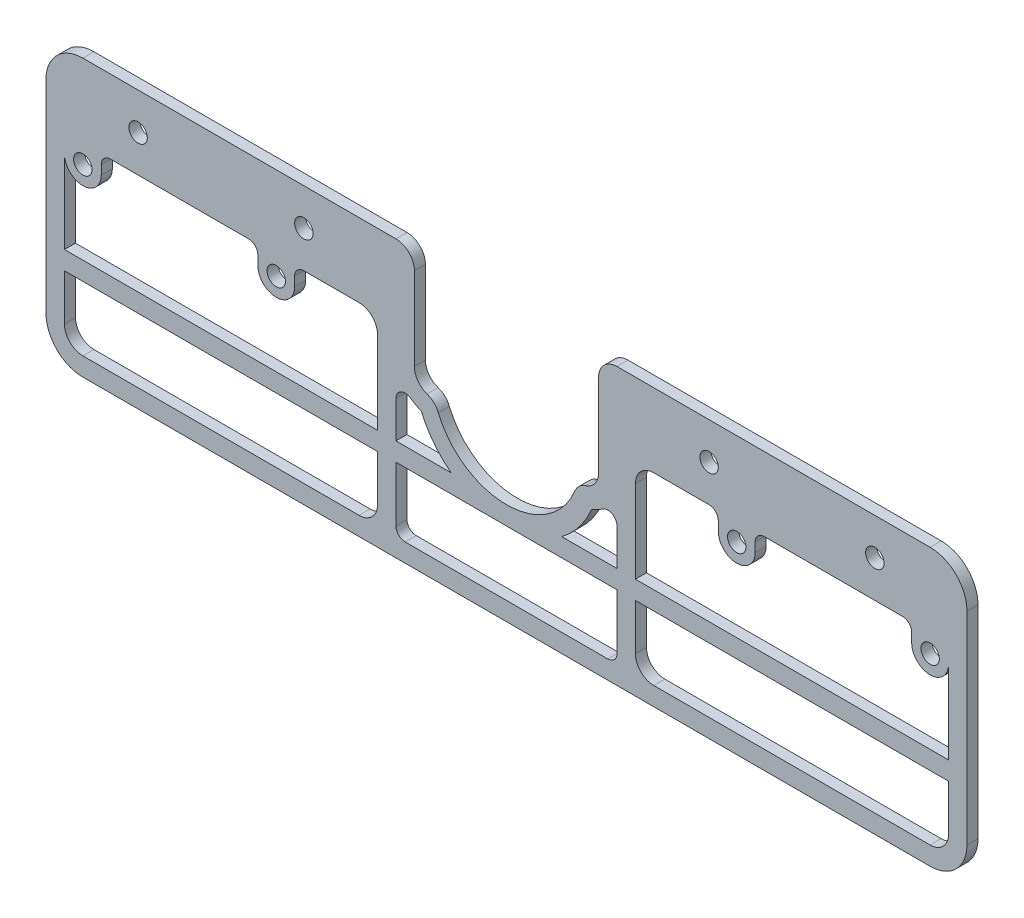
SolidWorks part; units mm, degrees
ref_plane "Front Plane" through (0, 0, 0) normal (0, 0, 1) x (1, 0, 0)
ref_plane "Top Plane" through (0, 0, 0) normal (0, 1, 0) x (1, 0, 0)
ref_plane "Right Plane" through (0, 0, 0) normal (1, 0, 0) x (0, 0, -1)
sketch "Sketch1" plane through (0, 0, 0) normal (0, 0, 1) x (1, 0, 0)
  line L0 (-40, 20) -> (-40, 55) construction
  line L4 (-250, -55) -> (-250, 3.1783)
  line L8 (-50, 75) -> (-230, 75) construction
  line L17 (0, -20) -> (0, -40)
  line L25 (0, -65) -> (0, -75)
  line L26 (0, 75) -> (0, -75) construction
  line L27 (-50, 95) -> (50, 95) construction
  line L34 (0, -75) -> (-230, -75)
  line L156 (-50, 75) -> (-230, 75) construction
  line L161 (0, -40) -> (0, -65)
  line L165 (-164.3309, 75) -> (-60, 75)
  line L167 (-230, 75) -> (-220, 75)
  line L171 (-250, 3.1783) -> (-250, 55)
  line L172 (-220, 75) -> (-164.3309, 75)
  line L173 (-50, 65) -> (-50, 20)
  arc A0 (-40, 20) -> (0, -20) centre (0, 20) ccw construction
  circle A1 centre (0, 20) radius 30 construction
  arc A4 (-230, -75) -> (-250, -55) centre (-230, -55) cw
  arc A5 (-250, 55) -> (-230, 75) centre (-230, 55) cw
  arc A124 (0, -20) -> (-37, 4.8013) centre (0, 20) cw
  arc A125 (-60, 75) -> (-50, 65) centre (-60, 65) cw
  arc A126 (-43.125, 10.5008) -> (-50, 20) centre (-40, 20) cw
  arc A127 (-37, 4.8013) -> (-43.125, 10.5008) centre (-46.25, 1.0016) ccw
  point P0 (0, 0)
  point P10 (-50, 10)
  point P11 (0, 50)
  point P30 (-40, 75)
  point P45 (0, -30)
  point P74 (0, 95)
  dimension "D3" = 80
  dimension "D4" = 60
  dimension "D6" = 55
  dimension "D7" = 75
  dimension "D10" = 10
  dimension "D11" = 20
  dimension "D8" = 10
  dimension "D5" = 10
  dimension "D9" = 20
  dimension "D13" = 210
  dimension "D16" = 100
  dimension "D17" = 20
  dimension "D26" = 250
extrude "Boss-Extrude1" add sketch "Sketch1" along normal blind 6
mirror "Mirror1" about plane through (0, -20, 6) normal (-1, 0, 0) of "Boss-Extrude1"
sketch "Sketch3" plane through (0, 0, 6) normal (0, 0, 1) x (1, 0, 0)
  line L3 (50, 20) -> (50, 65) construction
  line L4 (50, 20) -> (50, 65) construction
  line L7 (-60, 75) -> (-230, 75) construction
  line L8 (-250, 55) -> (-250, -55) construction
  line L9 (250, 55) -> (250, -55) construction
  circle A2 centre (110, 55) radius 5
  circle A3 centre (200, 55) radius 5
  circle A4 centre (-200, 55) radius 5
  circle A5 centre (-110, 55) radius 5
  dimension "D3" = 10
  dimension "D4" = 10
  dimension "D5" = 10
  dimension "D6" = 10
  dimension "D8" = 20
  dimension "D12" = 50
  dimension "D2" = 140
  dimension "D7" = 20
  dimension "D9" = 50
  dimension "D10" = 140
extrude "Cut-Extrude1" cut sketch "Sketch3" against normal through all contours A2 | A3 | A5 | A4
sketch "Sketch4" plane through (0, 0, 6) normal (0, 0, 1) x (1, 0, 0)
  line L0 (-230, -75) -> (230, -75) construction
  line L1 (-70, 25) -> (-70, -55)
  line L2 (-50, 20) -> (-50, 65) construction
  line L3 (-60, 75) -> (-230, 75) construction
  line L7 (-240, -55) -> (-240, 25)
  line L8 (-250, 55) -> (-250, -55) construction
  line L9 (-210, -65) -> (-190, -65)
  line L10 (-115, 25) -> (-115, 30)
  line L11 (-110, 35) -> (-80, 35)
  line L12 (-220, 25) -> (-220, 30)
  line L13 (-215, 35) -> (-140, 35)
  line L14 (-135, 30) -> (-135, 25)
  line L15 (-230, -65) -> (-210, -65)
  line L16 (-110, -65) -> (-90, -65)
  line L17 (0, 0) -> (0, -75) construction
  line L18 (-190, -65) -> (-110, -65)
  line L19 (90, -65) -> (80, -65)
  line L20 (190, -65) -> (110, -65)
  line L21 (-90, -65) -> (-80, -65)
  line L22 (110, -65) -> (90, -65)
  line L23 (230, -65) -> (210, -65)
  line L24 (230, 25) -> (125, 25) construction
  line L30 (221.3397, 20) -> (133.6603, 20)
  line L32 (110, 35) -> (80, 35)
  line L33 (115, 25) -> (115, 30)
  line L35 (210, -65) -> (190, -65)
  line L36 (240, -55) -> (240, 25)
  line L37 (70, 25) -> (70, -55)
  line L38 (125, 35) -> (230, 35)
  line L39 (230, 20) -> (125, 20) construction
  circle A0 centre (-230, 25) radius 5
  circle A3 centre (-125, 25) radius 5
  arc A6 (-230, -65) -> (-240, -55) centre (-230, -55) cw
  arc A8 (-222.2775, 18.6468) -> (-231.6408, 15.1355) centre (-230, 25) ccw
  arc A9 (-127.2754, 15.2623) -> (-127.1893, 15.2426) centre (-125, 25) ccw
  arc A12 (-110, 35) -> (-115, 30) centre (-110, 30) ccw
  arc A13 (-140, 35) -> (-135, 30) centre (-140, 30) cw
  arc A14 (-215, 35) -> (-220, 30) centre (-215, 30) ccw
  arc A15 (-70, -55) -> (-80, -65) centre (-80, -55) cw
  arc A16 (-70, 25) -> (-80, 35) centre (-80, 25) ccw
  arc A17 (-117.6445, 18.2253) -> (-134.5708, 22.1017) centre (-125, 25) ccw
  arc A19 (-231.6408, 15.1355) -> (-222.2775, 18.6468) centre (-230, 25) ccw
  arc A20 (-134.5708, 22.1017) -> (-117.3815, 18.5225) centre (-125, 25) ccw
  arc A21 (133.6603, 20) -> (117.3815, 18.5225) centre (125, 25) cw
  arc A22 (231.6408, 15.1355) -> (222.2775, 18.6468) centre (230, 25) cw
  arc A23 (117.6445, 18.2253) -> (125, 35) centre (125, 25) cw
  arc A24 (70, 25) -> (80, 35) centre (80, 25) cw
  arc A25 (70, -55) -> (80, -65) centre (80, -55) ccw
  arc A26 (230, 35) -> (231.6408, 15.1355) centre (230, 25) cw
  arc A28 (110, 35) -> (115, 30) centre (110, 30) cw
  arc A29 (127.2754, 15.2623) -> (127.1893, 15.2426) centre (125, 25) cw
  arc A30 (222.2775, 18.6468) -> (221.3397, 20) centre (230, 25) cw
  arc A31 (230, -65) -> (240, -55) centre (230, -55) ccw
  circle A32 centre (125, 25) radius 5
  circle A33 centre (230, 25) radius 5
  point P0 (0, -75)
  dimension "D1" = 10
  dimension "D13" = 10
  dimension "D14" = 20
  dimension "D10" = 5
  dimension "D15" = 5
  dimension "D17" = 10
  dimension "D2" = 230
  dimension "D4" = 5
  dimension "D5" = 125
  dimension "D8" = 50
  dimension "D9" = 10
  dimension "D11" = 20
  dimension "D12" = 80
  dimension "D16" = 80
extrude "Cut-Extrude2" cut sketch "Sketch4" against normal through all contours A20 A17 L14 A13 L13 A14 L12 A8 A19 L7 A6 L15 L9 L18 L16 L21 A15 L1 A16 L11 A12 L10 A9 | A0 | A3
sketch "Sketch8" plane through (0, 0, 6) normal (0, 0, 1) x (1, 0, 0)
  line L0 (-60, 0) -> (-60, -65)
  line L2 (-60, -65) -> (60, -65)
  line L3 (60, -65) -> (60, 0)
  line L4 (-230, -65) -> (-80, -65) construction
  arc A0 (43.125, 10.5008) -> (50, 20) centre (40, 20) ccw construction
  arc A1 (43.125, 10.5008) -> (37, 4.8013) centre (46.25, 1.0016) ccw construction
  arc A2 (-37, 4.8013) -> (-43.125, 10.5008) centre (-46.25, 1.0016) ccw construction
  arc A3 (-50, 20) -> (-43.125, 10.5008) centre (-40, 20) ccw construction
  arc A4 (-37, 4.8013) -> (37, 4.8013) centre (0, 20) ccw construction
  arc A5 (43.125, 10.5008) -> (50, 20) centre (40, 20) ccw construction
  arc A6 (43.125, 10.5008) -> (37, 4.8013) centre (46.25, 1.0016) ccw construction
  arc A7 (-37, 4.8013) -> (-43.125, 10.5008) centre (-46.25, 1.0016) ccw construction
  arc A8 (-50, 20) -> (-43.125, 10.5008) centre (-40, 20) ccw construction
  arc A9 (-37, 4.8013) -> (37, 4.8013) centre (0, 20) ccw construction
  arc A10 (-52, 4) -> (-46.25, 1.0016) centre (-40, 20) ccw
  arc A11 (-46.25, 1.0016) -> (-46.25, 1.0016) centre (-46.25, 1.0016) ccw
  arc A12 (-46.25, 1.0016) -> (46.25, 1.0016) centre (0, 20) ccw
  arc A13 (46.25, 1.0016) -> (46.25, 1.0016) centre (46.25, 1.0016) ccw
  arc A14 (46.25, 1.0016) -> (52, 4) centre (40, 20) ccw
  arc A15 (46.25, 1.0016) -> (60, 20) centre (40, 20) ccw construction
  arc A16 (60, 0) -> (52, 4) centre (55, 0) ccw
  arc A17 (-60, 20) -> (-46.25, 1.0016) centre (-40, 20) ccw construction
  arc A18 (-60, 0) -> (-52, 4) centre (-55, 0) cw
  dimension "D2" = 5
  dimension "D1" = 10
extrude "Cut-Extrude5" cut sketch "Sketch8" against normal through all
fillet "Fillet5" radius 5 1 edges at (-60, -65, 3)
fillet "Fillet6" radius 5 1 edges at (60, -65, 3)
mirror "Mirror2" about plane through (0, 0, 0) normal (1, 0, 0) of "Cut-Extrude2"
sketch "Sketch9" plane through (0, 0, 6) normal (0, 0, 1) x (1, 0, 0)
  line L0 (-250, -20) -> (250, -20)
  line L1 (-250, 55) -> (-250, -55) construction
  line L2 (250, 55) -> (250, -55) construction
  line L3 (250, -20) -> (250, -30)
  line L4 (250, -30) -> (-250, -30)
  line L5 (-250, -30) -> (-250, -20)
  arc A0 (-37, 4.8013) -> (37, 4.8013) centre (0, 20) ccw construction
  arc A1 (-46.25, 1.0016) -> (46.25, 1.0016) centre (0, 20) ccw construction
extrude "Boss-Extrude2" add sketch "Sketch9" against normal up to surface (6 mm away) up to face at (225, 25, 0)
